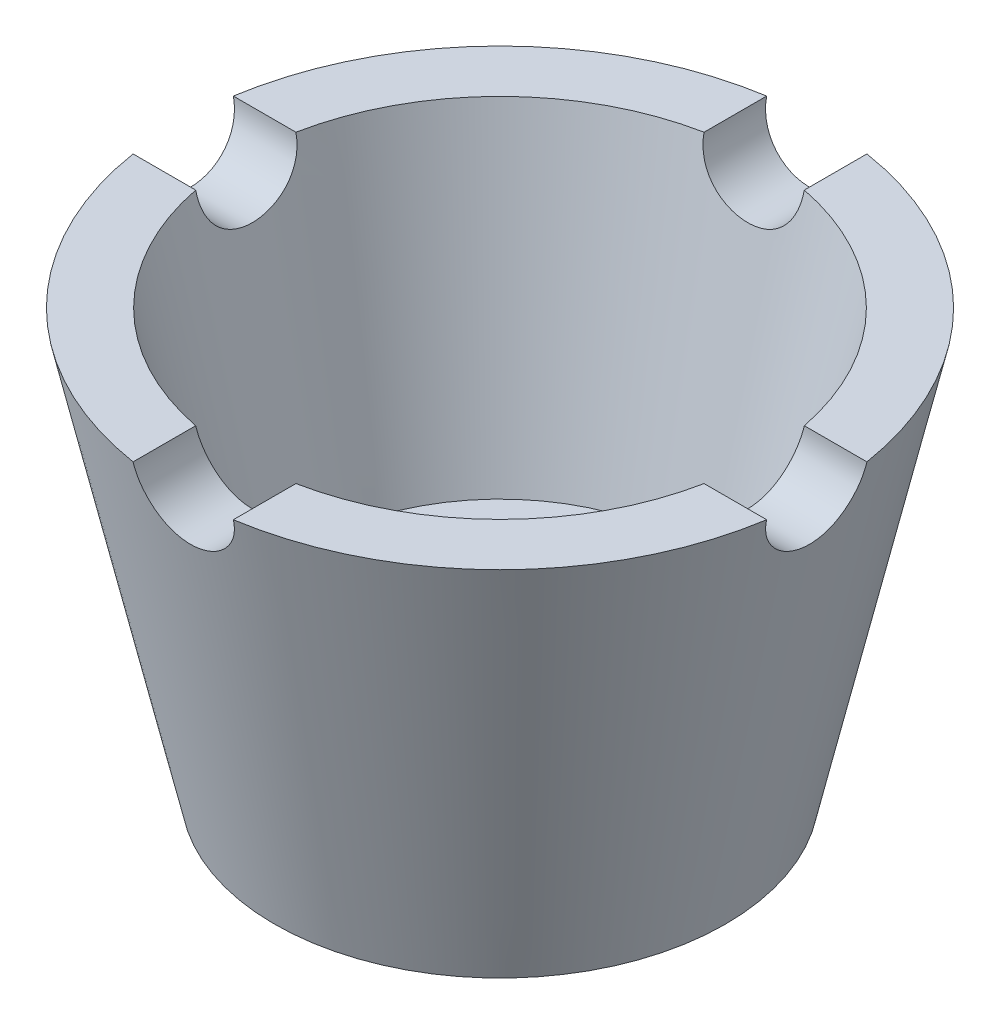
SolidWorks part; units mm, degrees
ref_plane "Front Plane" through (0, 0, 0) normal (0, 0, 1) x (1, 0, 0)
ref_plane "Top Plane" through (0, 0, 0) normal (0, 1, 0) x (1, 0, 0)
ref_plane "Right Plane" through (0, 0, 0) normal (1, 0, 0) x (0, 0, -1)
sketch "Sketch1" plane through (0, 0, 0) normal (0, 0, 1) x (1, 0, 0)
  line L0 (11.25, 0) -> (11.25, 12)
  line L1 (11.25, 12) -> (19.0627, 12)
  line L2 (19.0627, 12) -> (25.8484, 42)
  line L3 (25.8484, 42) -> (32, 42)
  line L4 (32, 42) -> (22.5, 0)
  line L5 (22.5, 0) -> (11.25, 0)
  line L6 (0, 0) -> (0, 43.2603) construction
  dimension "D1" = 11.25
  dimension "D2" = 22.5
  dimension "D3" = 32
  dimension "D4" = 6
  dimension "D5" = 12
  dimension "D6" = 42
revolve "Revolve1" add sketch "Sketch1" angle 360 about L6
sketch "Sketch2" plane through (0, 0, 0) normal (0, 0, 1) x (1, 0, 0)
  line L0 (25.8484, 42) -> (-25.8484, 42) construction
  line L1 (32, 42) -> (-32, 42) construction
  line L2 (5, 42) -> (-5, 42)
  arc A0 (-5, 42) -> (5, 42) centre (0, 42) ccw
  dimension "D1" = 5
extrude "Cut-Extrude1" cut sketch "Sketch2" against normal blind 10 and the other way through all
pattern_circular "CirPattern1" count 4 over 360 about axis through (0, 42, 0) along (0, -1, 0) of "Cut-Extrude1"
